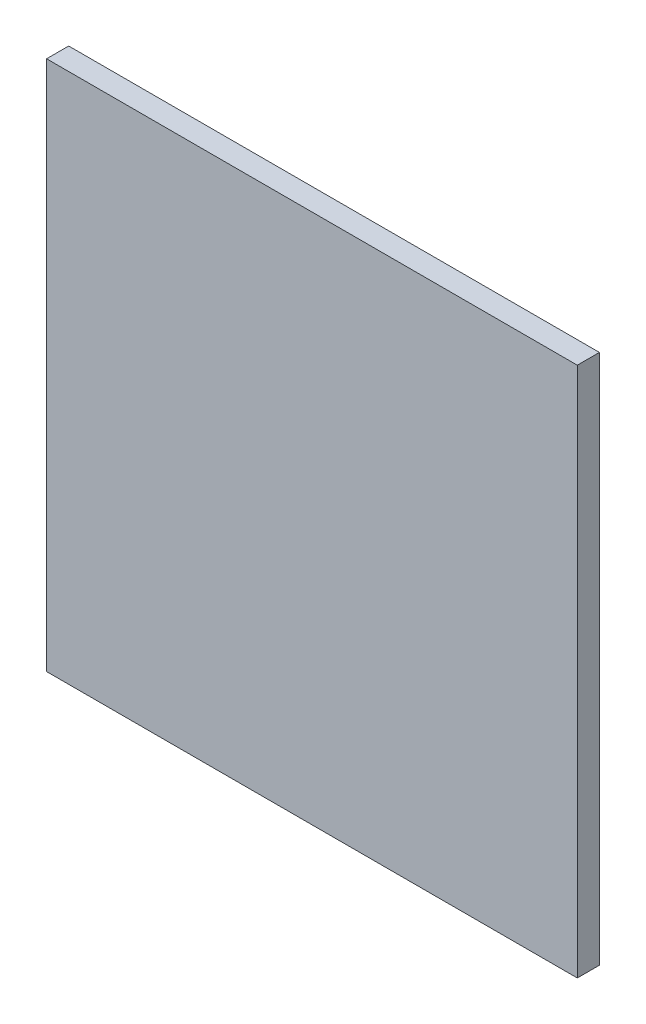
SolidWorks part; units mm, degrees
ref_plane "Front" through (0, 0, 0) normal (0, 0, 1) x (1, 0, 0)
ref_plane "Top" through (0, 0, 0) normal (0, 1, 0) x (1, 0, 0)
ref_plane "Right" through (0, 0, 0) normal (1, 0, 0) x (0, 0, -1)
sketch "Sketch1" plane through (0, 0, 0) normal (0, 0, 1) x (1, 0, 0)
  line L0 (0, 0) -> (0, 30) construction
  line L1 (0, 0) -> (30, 0) construction
  line L3 (-30, 30) -> (30, 30)
  line L4 (-30, 30) -> (-30, -30)
  line L5 (-30, -30) -> (30, -30)
  line L6 (30, 30) -> (30, -30)
  dimension "D1" = 60
extrude "Boss-Extrude1" add sketch "Sketch1" along normal blind 2.5
